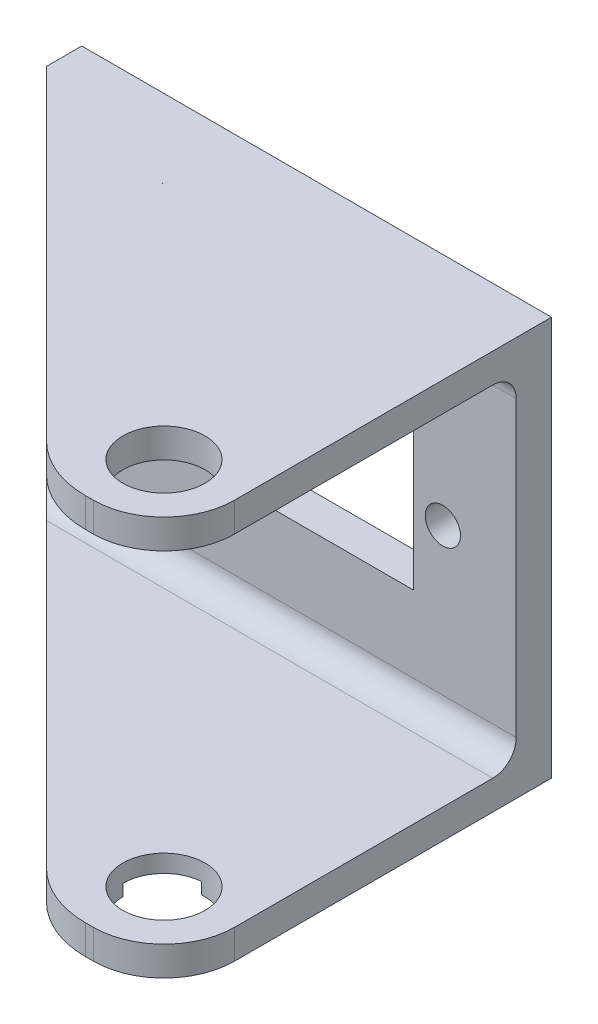
SolidWorks part; units mm, degrees
ref_plane "Plano frontal" through (0, 0, 0) normal (0, 0, 1) x (1, 0, 0)
ref_plane "Plano superior" through (0, 0, 0) normal (0, 1, 0) x (1, 0, 0)
ref_plane "Plano direito" through (0, 0, 0) normal (1, 0, 0) x (0, 0, -1)
sketch "Esboço1" plane through (0, 0, 0) normal (0, 0, 1) x (1, 0, 0)
  line L0 (-2.1016, 17.4595) -> (-2.1016, -16.5405) construction
  line L1 (-13.3516, 6.4595) -> (9.1484, 6.4595)
  line L2 (-13.3516, 6.4595) -> (-13.3516, -5.5405)
  line L3 (-13.3516, -5.5405) -> (9.1484, -5.5405)
  line L4 (9.1484, 6.4595) -> (9.1484, -5.5405)
  line L5 (-22.1016, 17.4595) -> (17.8984, 17.4595)
  line L6 (-22.1016, 17.4595) -> (-22.1016, -16.5405)
  line L7 (-22.1016, -16.5405) -> (17.8984, -16.5405)
  line L8 (17.8984, 17.4595) -> (17.8984, -16.5405)
  line L9 (-22.1016, 0.4595) -> (17.8984, 0.4595) construction
  line L10 (-22.1016, 17.4595) -> (17.8984, -16.5405) construction
  circle A0 centre (-16.1016, 12.3595) radius 1.5
  circle A1 centre (-16.1016, -11.4405) radius 1.5
  circle A2 centre (11.8984, -11.4405) radius 1.5
  circle A3 centre (11.8984, 12.3595) radius 1.5
  circle A4 centre (11.6484, 0.4595) radius 1.5
  circle A5 centre (-15.8516, 0.4595) radius 1.5
  point P10 (-2.1016, 6.4595)
  point P13 (-13.3516, 0.4595)
  point P24 (10.1484, 0.4595)
  dimension "D5" = 6
  dimension "D6" = 1
  dimension "D1" = 22.5
  dimension "D2" = 12
  dimension "D3" = 40
  dimension "D4" = 34
extrude "Ressalto-extrusão1" add sketch "Esboço1" along normal blind 3 contours A5 | L6 L5 L8 L7 | A4 | L2 L1 L4 L3
sketch "Esboço2" plane through (0, 0, 3) normal (0, 0, 1) x (1, 0, 0)
  line L0 (-22.1016, 14.9595) -> (17.8984, 14.9595) construction
  line L1 (-22.1016, 17.4595) -> (-22.1016, -16.5405) construction
  line L2 (17.8984, 17.4595) -> (17.8984, -16.5405) construction
  line L3 (-22.1016, 0.4595) -> (17.8984, 0.4595) construction
  line L4 (-22.1016, 17.4595) -> (17.8984, 17.4595) construction
  line L5 (-22.1016, 17.4595) -> (17.8984, 17.4595) construction
  line L6 (-22.1016, 17.4595) -> (-22.1016, 14.9595)
  line L7 (-22.1016, 14.9595) -> (17.8984, 14.9595)
  line L8 (17.8984, 14.9595) -> (17.8984, 17.4595)
  line L9 (17.8984, 17.4595) -> (-22.1016, 17.4595)
  line L10 (17.8984, -14.0405) -> (17.8984, -16.5405)
  line L11 (-22.1016, -14.0405) -> (17.8984, -14.0405)
  line L12 (-22.1016, -16.5405) -> (-22.1016, -14.0405)
  line L13 (17.8984, -16.5405) -> (-22.1016, -16.5405)
  dimension "D1" = 2.5
  dimension "D2" = 2.5
extrude "Ressalto-extrusão2" add sketch "Esboço2" along normal blind 30
sketch "Esboço3" plane through (0, -16.5405, 0) normal (0, -1, 0) x (1, 0, 0)
  line L0 (-22.1016, 3) -> (17.8984, 3) construction
  line L1 (-22.1016, 33) -> (-22.1016, 0) construction
  line L2 (17.8984, 33) -> (17.8984, 0) construction
  line L3 (-22.1016, 0) -> (17.8984, 0) construction
  line L4 (-22.1016, 3) -> (-22.1016, 8) construction
  line L6 (-22.1016, 33) -> (17.8984, 33) construction
  line L7 (7.8984, 33) -> (17.8984, 33) construction
  line L8 (17.8984, 33) -> (17.8984, 3) construction
  line L9 (-22.1016, 3) -> (7.8984, 33)
  line L11 (-22.1016, 33) -> (7.8984, 33)
  line L13 (-22.1016, 3) -> (-22.1016, 33)
  circle A0 centre (11.8984, 27) radius 3.5
  dimension "D4" = 6
  dimension "D5" = 6
  dimension "D1" = 3
  dimension "D3" = 10
extrude "Corte-extrusão1" cut sketch "Esboço3" against normal through all both and the other way through all
fillet "Filete1" radius 6 2 edges at (17.8984, 16.2095, 33) (17.8984, -15.2905, 33)
fillet "Filete2" radius 2 2 edges at (-2.1016, -14.0405, 3) (-2.1016, 14.9595, 3)
sketch "Esboço4" plane through (0, -16.5405, 0) normal (0, -1, 0) x (1, 0, 0)
  line L0 (8.3984, 27) -> (-2.1579, 16.3433)
  line L1 (-2.1579, 16.3433) -> (1.2134, 13.0038)
  line L2 (1.2134, 13.0038) -> (11.6216, 23.511)
  line L3 (8.3984, 27) -> (11.6216, 23.511)
  circle A0 centre (11.8984, 27) radius 3.5 construction
  dimension "D1" = 15
  dimension "D2" = 4.75
extrude "Corte-extrusão2" cut sketch "Esboço4" against normal blind 1
fillet "Filete4" radius 8 2 edges at (7.8984, -15.2905, 33) (7.8984, 16.2095, 33)
